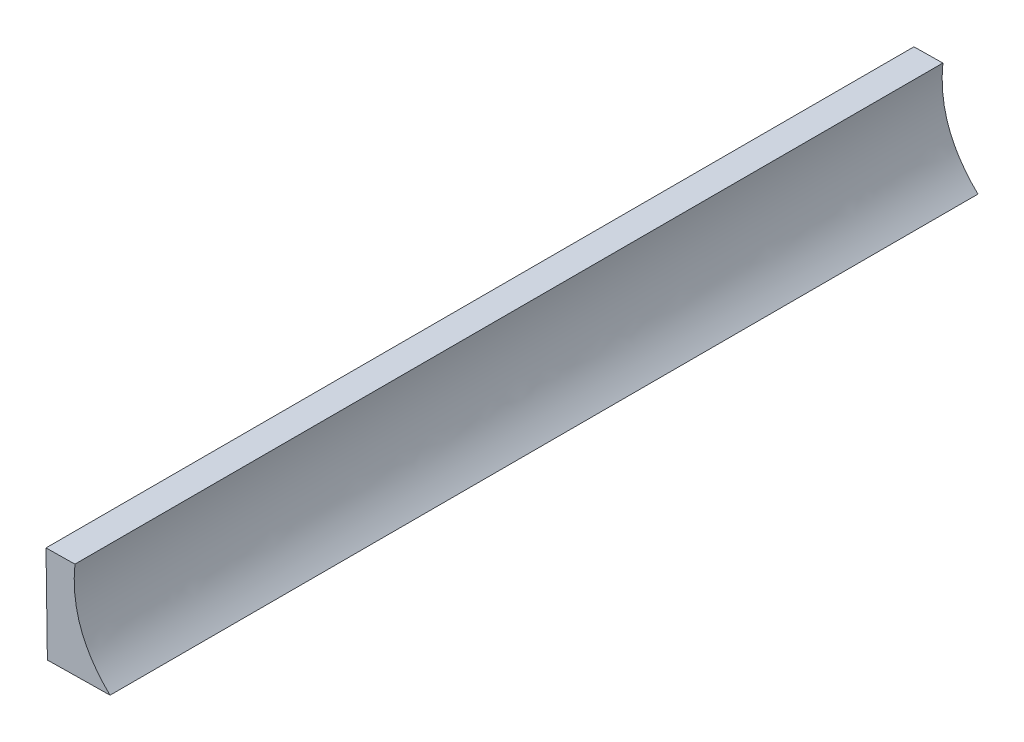
SolidWorks part; units mm, degrees
ref_plane "Plan de face" through (0, 0, 0) normal (0, 0, 1) x (1, 0, 0)
ref_plane "Plan de dessus" through (0, 0, 0) normal (0, 1, 0) x (1, 0, 0)
ref_plane "Plan de droite" through (0, 0, 0) normal (1, 0, 0) x (0, 0, -1)
sketch "Esquisse1" plane through (0, 0, 0) normal (0, 0, 1) x (1, 0, 0)
  line L0 (-55.4984, 21.3682) -> (-49.4984, 21.4541)
  line L1 (-55.2119, 1.3702) -> (-42.2119, 1.5565)
  line L2 (-55.4984, 21.3682) -> (-55.2119, 1.3702)
  spline S0 degree 2 poles (-49.4984, 21.4541) (-50.7103, 9.6153) (-42.2119, 1.5565) knots 0 0 0 1 1 1
  dimension "D1" = 6
  dimension "D2" = 13
  dimension "D3" = 20
extrude "Boss.-Extru.1" add sketch "Esquisse1" along normal blind 180 contours L2 L1 S0 L0
